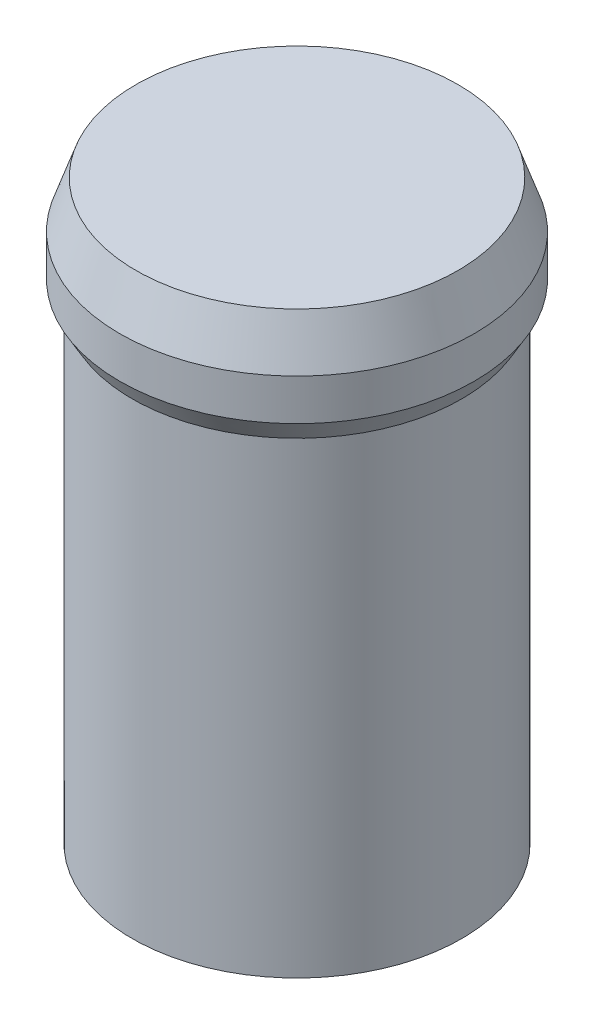
SolidWorks part; units mm, degrees
ref_plane "Front Plane" through (0, 0, 0) normal (0, 0, 1) x (1, 0, 0)
ref_plane "Top Plane" through (0, 0, 0) normal (0, 1, 0) x (1, 0, 0)
ref_plane "Right Plane" through (0, 0, 0) normal (1, 0, 0) x (0, 0, -1)
sketch "Sketch1" plane through (0, 0, 0) normal (0, 0, 1) x (1, 0, 0)
  line L0 (20, 0) -> (20, 56.7271)
  line L1 (20, 56.7271) -> (21.5, 59.3252)
  line L2 (21.5, 59.3252) -> (21.5, 64.3252)
  line L3 (21.5, 64.3252) -> (19.5473, 69.9985)
  line L4 (20, 0) -> (19, 0)
  line L5 (19, 0) -> (19, 1.15)
  line L6 (6.7, 1.15) -> (19, 1.15)
  line L7 (0, 2.4) -> (0, 83.9789) construction
  line L8 (6.7, 2.4) -> (0, 2.4)
  line L9 (6.7, 2.4) -> (6.7, 1.15)
  line L11 (19.5473, 69.9985) -> (0, 69.9985)
  line L12 (0, 69.9985) -> (0, 2.4)
  point P12 (0, 0)
  point P14 (0, 0)
  dimension "D1" = 20
  dimension "D2" = 1
  dimension "D3" = 6.7
  dimension "D4" = 70
  dimension "D5" = 5
  dimension "D6" = 1.5
  dimension "D7" = 3
  dimension "D8" = 6
  dimension "D9" = 1.15
  dimension "D10" = 1.25
revolve "Revolve1" add sketch "Sketch1" angle 360 about L7
